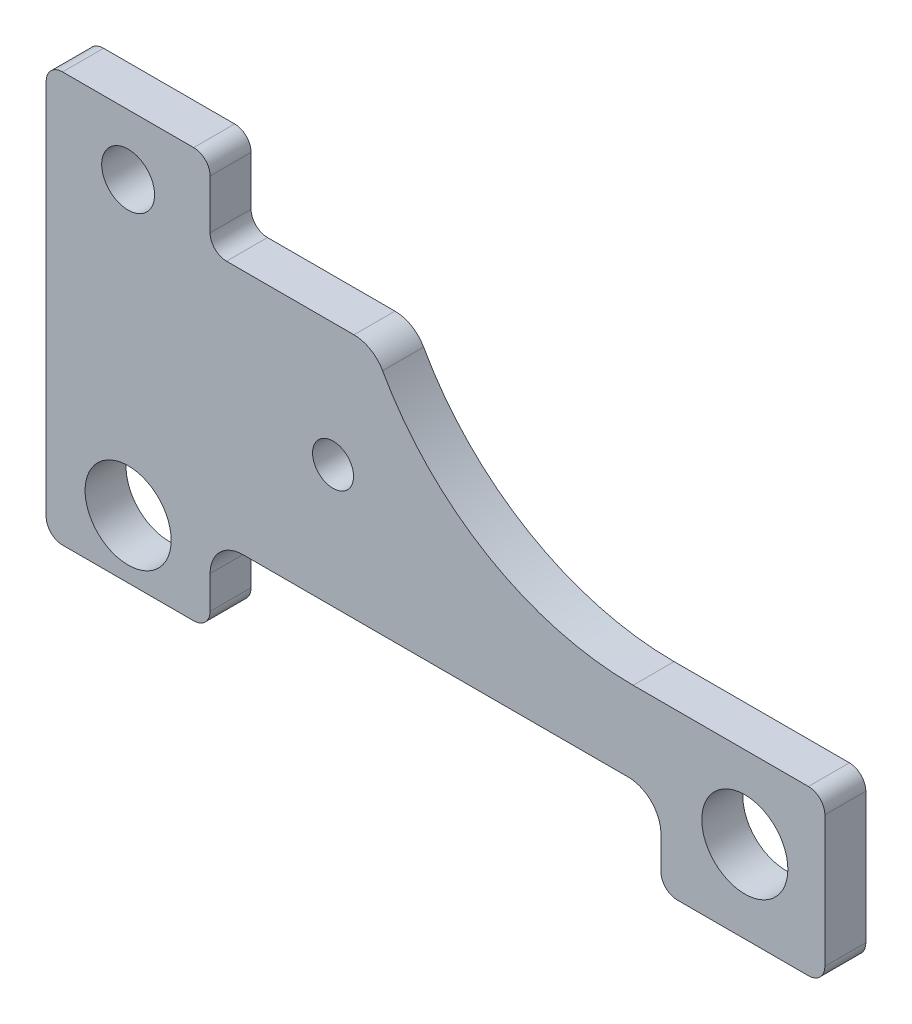
SolidWorks part; units mm, degrees
ref_plane "Plano frontal" through (0, 0, 0) normal (0, 0, 1) x (1, 0, 0)
ref_plane "Plano superior" through (0, 0, 0) normal (0, 1, 0) x (1, 0, 0)
ref_plane "Plano direito" through (0, 0, 0) normal (1, 0, 0) x (0, 0, -1)
sketch "Esboço1" plane through (0, 0, 0) normal (0, 0, 1) x (1, 0, 0)
  line L0 (0.2381, -10.7143) -> (31.2381, -10.7143)
  line L1 (-37.7619, 29.2857) -> (-21.7619, 29.2857)
  line L2 (-39.7619, 27.2857) -> (-39.7619, -18.7143)
  line L3 (-37.7619, -20.7143) -> (-21.7619, -20.7143)
  line L4 (-19.7619, 27.2857) -> (-19.7619, 21.2857)
  line L5 (-17.7619, 19.2857) -> (-2.211, 19.2857)
  line L7 (-15.7619, -10.7143) -> (0.2381, -10.7143)
  line L9 (31.8478, -0.7143) -> (53.2381, -0.7143)
  line L10 (35.2381, -14.7143) -> (35.2381, -18.7143)
  line L11 (37.2381, -20.7143) -> (53.2381, -20.7143)
  line L12 (55.2381, -2.7143) -> (55.2381, -18.7143)
  line L13 (-19.7619, -14.7143) -> (-19.7619, -18.7143)
  arc A0 (1.2823, 17.2344) -> (31.8478, -0.7143) centre (31.8478, 34.2857) ccw
  circle A1 centre (-29.7619, -13.5714) radius 5.25
  circle A2 centre (-29.7619, 21.9048) radius 3.225
  circle A3 centre (-4.7619, 4.2857) radius 2.5
  circle A4 centre (45.4762, -10.7143) radius 5.25
  arc A5 (31.2381, -10.7143) -> (35.2381, -14.7143) centre (31.2381, -14.7143) cw
  arc A6 (-19.7619, -14.7143) -> (-15.7619, -10.7143) centre (-15.7619, -14.7143) cw
  arc A7 (-2.211, 19.2857) -> (1.2823, 17.2344) centre (-2.211, 15.2857) cw
  arc A8 (-21.7619, 29.2857) -> (-19.7619, 27.2857) centre (-21.7619, 27.2857) cw
  arc A9 (-17.7619, 19.2857) -> (-19.7619, 21.2857) centre (-17.7619, 21.2857) cw
  arc A10 (-37.7619, 29.2857) -> (-39.7619, 27.2857) centre (-37.7619, 27.2857) ccw
  arc A11 (-39.7619, -18.7143) -> (-37.7619, -20.7143) centre (-37.7619, -18.7143) ccw
  arc A12 (-21.7619, -20.7143) -> (-19.7619, -18.7143) centre (-21.7619, -18.7143) ccw
  arc A13 (53.2381, -0.7143) -> (55.2381, -2.7143) centre (53.2381, -2.7143) cw
  arc A14 (53.2381, -20.7143) -> (55.2381, -18.7143) centre (53.2381, -18.7143) ccw
  arc A15 (35.2381, -18.7143) -> (37.2381, -20.7143) centre (37.2381, -18.7143) ccw
  point P12 (45.2381, -20.7143)
  point P28 (-19.7619, -10.7143)
  point P35 (-19.7619, 19.2857)
  point P38 (-39.7619, 29.2857)
  point P41 (-39.7619, -20.7143)
  point P44 (-19.7619, -20.7143)
  point P47 (55.2381, -0.7143)
  point P50 (55.2381, -20.7143)
  point P53 (35.2381, -20.7143)
  dimension "D12" = 35
  dimension "D13" = 10.5
  dimension "D14" = 6.45
  dimension "D15" = 5
  dimension "D16" = 10
  dimension "D5" = 4
  dimension "D20" = 2
  dimension "D21" = 2
  dimension "D22" = 2
  dimension "D23" = 2
  dimension "D24" = 2
  dimension "D1" = 20
  dimension "D2" = 50
  dimension "D3" = 20
  dimension "D4" = 30
  dimension "D6" = 10
  dimension "D7" = 20
  dimension "D8" = 20
  dimension "D9" = 0
  dimension "D10" = 55
  dimension "D11" = 95
  dimension "D17" = 10
  dimension "D18" = 25
  dimension "D19" = 15
extrude "Ressalto-extrusão1" add sketch "Esboço1" along normal blind 5
